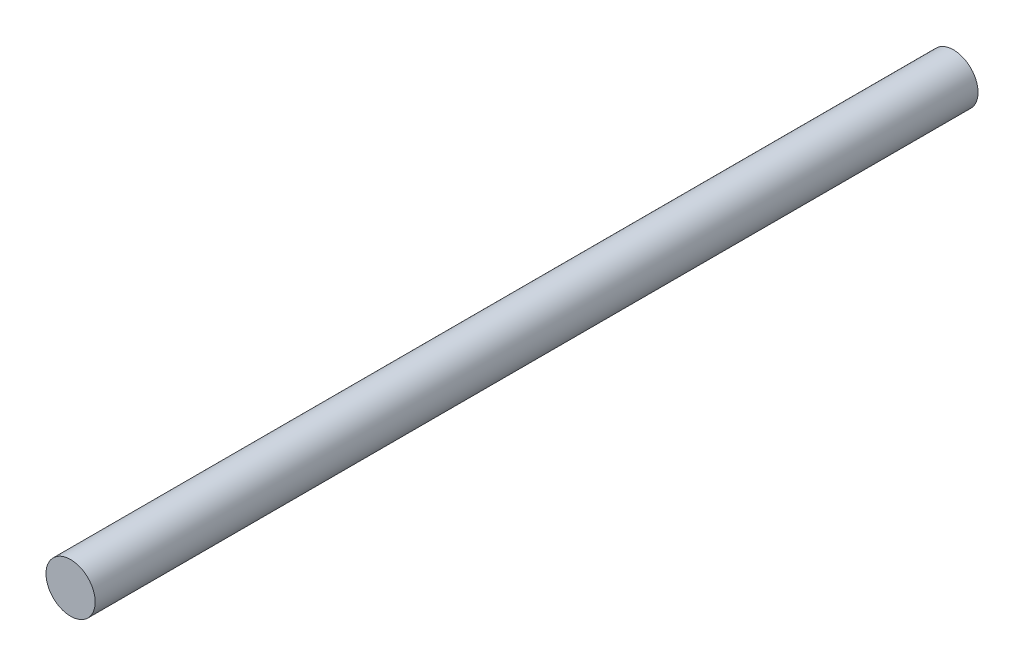
SolidWorks part; units mm, degrees
ref_plane "Front Plane" through (0, 0, 0) normal (0, 0, 1) x (1, 0, 0)
ref_plane "Top Plane" through (0, 0, 0) normal (0, 1, 0) x (1, 0, 0)
ref_plane "Right Plane" through (0, 0, 0) normal (1, 0, 0) x (0, 0, -1)
sketch "Sketch1" plane through (0, 0, 0) normal (0, 0, 1) x (1, 0, 0)
  circle A0 centre (0, 0) radius 1.5875
  dimension "D1" = 3.175
extrude "Boss-Extrude1" add sketch "Sketch1" along normal blind 57
